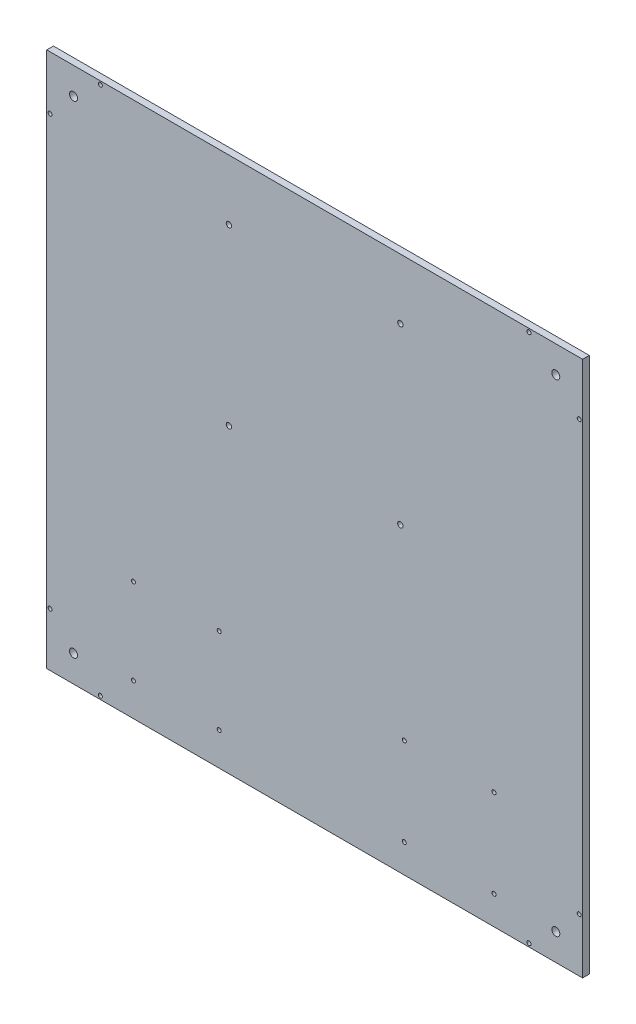
SolidWorks part; units mm, degrees
ref_plane "Front Plane" through (0, 0, 0) normal (0, 0, 1) x (1, 0, 0)
ref_plane "Top Plane" through (0, 0, 0) normal (0, 1, 0) x (1, 0, 0)
ref_plane "Right Plane" through (0, 0, 0) normal (1, 0, 0) x (0, 0, -1)
sketch "Sketch1" plane through (0, 0, 0) normal (0, 0, 1) x (1, 0, 0)
  line L1 (0, 0) -> (400, 0)
  line L2 (0, 0) -> (0, 400)
  line L3 (0, 400) -> (400, 400)
  line L4 (400, 0) -> (400, 400)
  line L5 (129, 362) -> (271, 362)
  line L6 (129, 362) -> (129, 218)
  line L7 (129, 218) -> (271, 218)
  line L8 (271, 362) -> (271, 218)
  circle A0 centre (20, 380) radius 3
  circle A1 centre (20, 20) radius 3
  circle A2 centre (380, 20) radius 3
  circle A3 centre (380, 380) radius 3
  circle A4 centre (136, 355) radius 2
  circle A5 centre (136, 225) radius 2
  circle A6 centre (264, 225) radius 2
  circle A7 centre (264, 355) radius 2
  circle A8 centre (40, 2.5) radius 1.5
  circle A9 centre (2.5, 40) radius 1.5
  circle A10 centre (2.5, 360) radius 1.5
  circle A11 centre (397.5, 360) radius 1.5
  circle A12 centre (360, 2.5) radius 1.5
  circle A13 centre (40, 397.5) radius 1.5
  circle A14 centre (360, 397.5) radius 1.5
  circle A15 centre (397.5, 40) radius 1.5
  circle A16 centre (333.89, 21.385) radius 1.5
  circle A17 centre (266.89, 21.385) radius 1.5
  circle A18 centre (266.89, 87.056) radius 1.5
  circle A19 centre (333.89, 87.056) radius 1.5
  circle A24 centre (128.75, 24.663) radius 1.5
  circle A25 centre (64.755, 24.66) radius 1.5
  circle A26 centre (128.75, 88.663) radius 1.5
  circle A27 centre (64.75, 88.66) radius 1.5
  dimension "D3" = 20
  dimension "D6" = 20
  dimension "D7" = 20
  dimension "D8" = 20
  dimension "D9" = 20
  dimension "D10" = 20
  dimension "D13" = 7
  dimension "D16" = 7
  dimension "D17" = 7
  dimension "D18" = 7
  dimension "D23" = 2.5
  dimension "D27" = 2.5
  dimension "D33" = 40
  dimension "D47" = 64
  dimension "D51" = 21.385
  dimension "D52" = 21.385
  dimension "D53" = 24.66
  dimension "D54" = 65.671
  dimension "D56" = 66.11
  dimension "D55" = 66.11
  dimension "D57" = 67
  dimension "D46" = 64
  dimension "D1" = 400
  dimension "D2" = 400
  dimension "D4" = 20
  dimension "D5" = 20
  dimension "D11" = 142
  dimension "D12" = 144
  dimension "D14" = 7
  dimension "D15" = 7
  dimension "D19" = 7
  dimension "D20" = 7
  dimension "D21" = 129
  dimension "D22" = 38
  dimension "D24" = 40
  dimension "D25" = 2.5
  dimension "D26" = 40
  dimension "D28" = 40
  dimension "D29" = 2.5
  dimension "D30" = 40
  dimension "D31" = 2.5
  dimension "D32" = 40
  dimension "D34" = 2.5
  dimension "D35" = 2.5
  dimension "D36" = 40
  dimension "D37" = 40
  dimension "D38" = 2.5
extrude "Boss-Extrude1" add sketch "Sketch1" along normal blind 5 contours L1 L4 L3 L2 A3 A2 A1 A0 L5 L8 L7 L6 | L8 L5 L6 L7 A7 A6 A5 A4
